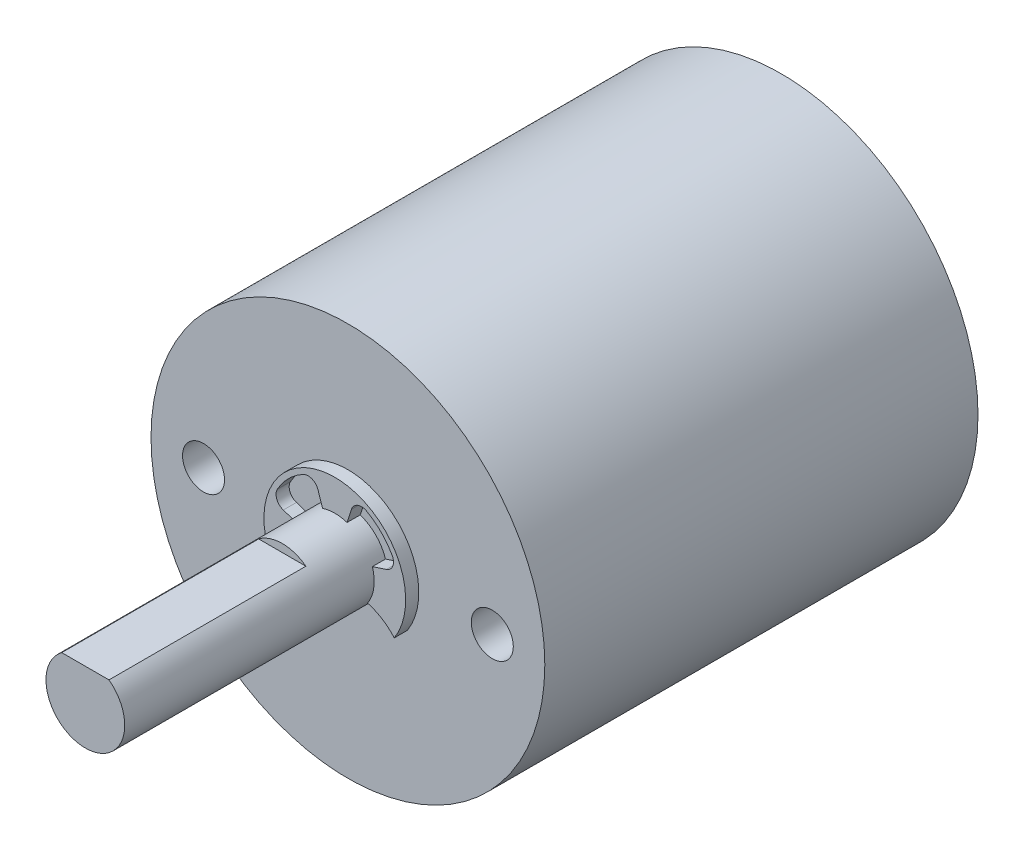
SolidWorks part; units mm, degrees
ref_plane "前视基准面" through (0, 0, 0) normal (0, 0, 1) x (1, 0, 0)
ref_plane "上视基准面" through (0, 0, 0) normal (0, 1, 0) x (1, 0, 0)
ref_plane "右视基准面" through (0, 0, 0) normal (1, 0, 0) x (0, 0, -1)
sketch "草图1" plane through (0, 0, 0) normal (0, 0, 1) x (1, 0, 0)
  circle A0 centre (0, 0) radius 7.5
extrude "凸台-拉伸1" add sketch "草图1" along normal blind 16.5
sketch "草图2" plane through (0, 0, 16.5) normal (0, 0, 1) x (1, 0, 0)
  circle A0 centre (0, 0) radius 1.5
extrude "凸台-拉伸2" add sketch "草图2" along normal blind 10
sketch "草图3" plane through (0, 0, 26.5) normal (0, 0, 1) x (1, 0, 0)
  line L0 (0, 1.5) -> (0, 1.2) construction
  line L1 (0, 1.2) -> (2.1676, 1.2) construction
  line L2 (2.1676, 1.2) -> (-1.6312, 1.2)
  line L3 (-1.6312, 1.2) -> (-1.6312, 1.7112)
  line L4 (-1.6312, 1.7112) -> (2.1676, 1.7112)
  line L5 (2.1676, 1.7112) -> (2.1676, 1.2)
  circle A0 centre (0, 0) radius 1.5 construction
extrude "切除-拉伸1" cut sketch "草图3" against normal blind 7.5
sketch "草图4" plane through (0, 0, 16.5) normal (0, 0, 1) x (1, 0, 0)
  circle A0 centre (0, 0) radius 5.5 construction
  circle A1 centre (5.5, 0) radius 1
  circle A2 centre (-5.5, 0) radius 1
hole_wizard "M2 螺纹孔1" positions "3D草图1" profile "草图5" tap size "M2" standard "GB"
sketch3d "3D草图1"
  point P0 (5.5, 0, 16.5)
  point P3 (-5.5, 0, 16.5)
sketch "草图5" plane through (5.5, 0, 16.5) normal (1, 0, 0) x (0, -1, 0)
  line L0 (0, 0) -> (0, 6.4619)
  line L1 (0, 6.4619) -> (0.8, 6)
  line L2 (0.8, 6) -> (0.8, 0)
  line L5 (0.8, 0) -> (0, 0)
  line L10 (0, 6.4619) -> (-0.8, 6) construction
  line L11 (0, -6.35) -> (0, 107.95) construction
  dimension "螺纹孔钻头直径" = 1.6
  dimension "螺纹孔钻头深度" = 6
  dimension "导头角度" = 120
cosmetic thread "孔螺蚊线1" parameters "D1"=4, "D2"=2
cosmetic thread "孔螺蚊线2" parameters "D1"=4, "D2"=2
sketch "草图7" plane through (0, 0, 16.5) normal (0, 0, 1) x (1, 0, 0)
  line L0 (1.9609, 0.6236) -> (1.4269, 0.4501)
  line L3 (-1.4263, 0.4501) -> (-1.9604, 0.6236)
  line L4 (-0.6368, 1.9472) -> (-0.4632, 1.4131)
  line L5 (0.4638, 1.4131) -> (0.6373, 1.9472)
  line L6 (2.2985, -0.1038) -> (2.2985, -0.1038)
  line L9 (-2.2979, -0.1038) -> (-2.2979, -0.1038)
  line L10 (0.0003, 2.4598) -> (0.0003, 2.4598)
  line L11 (0.0003, 2.4598) -> (0.0003, 2.4598)
  line L12 (-1.7011, -2.4169) -> (-1.2497, -0.8426) construction
  line L13 (1.2503, -0.8426) -> (1.7017, -2.4169) construction
  line L14 (-2.2653, -1.4821) -> (-2.1079, -0.933) construction
  line L15 (2.1085, -0.933) -> (2.2659, -1.4821) construction
  arc A0 (1.9609, 0.6236) -> (2.1872, 1.1978) centre (1.8373, 1.004) ccw
  arc A1 (1.2503, -0.8426) -> (1.4269, 0.4501) centre (0.0003, -0.0135) ccw
  arc A5 (-1.4263, 0.4501) -> (-1.2497, -0.8426) centre (0.0003, -0.0135) ccw
  arc A6 (-2.1867, 1.1978) -> (-1.9604, 0.6236) centre (-1.8368, 1.004) ccw
  arc A7 (-1.211, 2.1735) -> (-2.1867, 1.1978) centre (0.0003, -0.0135) ccw
  arc A8 (-0.6368, 1.9472) -> (-1.211, 2.1735) centre (-1.0172, 1.8236) ccw
  arc A9 (0.4638, 1.4131) -> (-0.4632, 1.4131) centre (0.0003, -0.0135) ccw
  arc A10 (1.2116, 2.1735) -> (0.6373, 1.9472) centre (1.0178, 1.8236) ccw
  arc A11 (2.1872, 1.1978) -> (1.2116, 2.1735) centre (0.0003, -0.0135) ccw
  arc A13 (2.2659, -1.4821) -> (2.2659, -1.4821) centre (2.2659, -1.4821) ccw
  arc A14 (2.2659, -1.4821) -> (-2.2653, -1.4821) centre (0.0003, -0.0135) ccw
  arc A15 (-2.2653, -1.4821) -> (-2.2653, -1.4821) centre (-2.2653, -1.4821) ccw
  arc A18 (0.0003, 2.4598) -> (-1.5986, 2.8733) centre (-1.0172, 1.8236) ccw construction
  arc A19 (-2.2979, -0.1038) -> (-2.1079, -0.933) centre (0.0003, -0.0135) ccw construction
  arc A20 (0.0003, 2.4598) -> (0.0003, 2.4598) centre (0.0003, 2.4598) cw
  arc A24 (2.3554, -2.6026) -> (-2.3548, -2.6026) centre (0.0003, -0.0135) ccw construction
  arc A25 (-1.5986, 2.8733) -> (-2.8865, 1.5854) centre (0.0003, -0.0135) ccw construction
  arc A26 (-2.8865, 1.5854) -> (-2.2979, -0.1038) centre (-1.8368, 1.004) ccw construction
  arc A27 (1.7017, -2.4169) -> (2.3554, -2.6026) centre (2.0862, -2.3067) ccw construction
  arc A28 (-2.3548, -2.6026) -> (-1.7011, -2.4169) centre (-2.0856, -2.3067) ccw construction
  arc A29 (1.5992, 2.8733) -> (0.0003, 2.4598) centre (1.0178, 1.8236) ccw construction
  arc A30 (2.8871, 1.5854) -> (1.5992, 2.8733) centre (0.0003, -0.0135) ccw construction
  arc A31 (2.2985, -0.1038) -> (2.8871, 1.5854) centre (1.8373, 1.004) ccw construction
  arc A32 (2.1085, -0.933) -> (2.2985, -0.1038) centre (0.0003, -0.0135) ccw construction
  spline S1 degree 2 poles (-2.2653, -1.4821) (-1.9354, -0.8303) (-1.2497, -0.8426) knots 0 0 0 1 1 1
  spline S2 degree 2 poles (1.2503, -0.8426) (1.8501, -1.0114) (2.2659, -1.4821) knots 0 0 0 1 1 1
  dimension "D1" = 0.8
extrude "凸台-拉伸3" add sketch "草图7" along normal blind 0.5 contours A14 A13 S2 A1 L0 A0 A11 A10 L5 A9 L4 A8 A7 A6 L3 A5 S1
